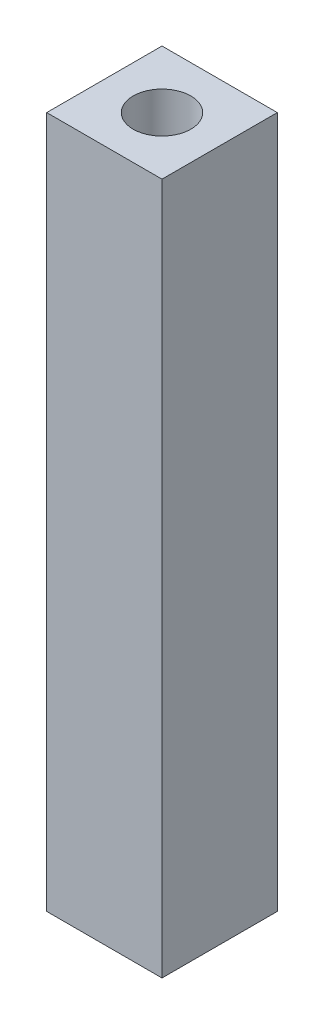
SolidWorks part; units mm, degrees
material "6061 Alloy"
ref_plane "Front Plane" through (0, 0, 0) normal (0, 0, 1) x (1, 0, 0)
ref_plane "Top Plane" through (0, 0, 0) normal (0, 1, 0) x (1, 0, 0)
ref_plane "Right Plane" through (0, 0, 0) normal (1, 0, 0) x (0, 0, -1)
sketch "Sketch1" plane through (0, 0, 0) normal (0, 1, 0) x (1, 0, 0)
  line L1 (-5, 5) -> (5, 5)
  line L2 (-5, 5) -> (-5, -5)
  line L3 (-5, -5) -> (5, -5)
  line L4 (5, 5) -> (5, -5)
  line L5 (-5, 5) -> (5, -5) construction
  line L6 (-5, -5) -> (5, 5) construction
  point P0 (0, 0)
  dimension "D1" = 10
  dimension "D2" = 10
extrude "Boss-Extrude1" add sketch "Sketch1" along normal blind 60
sketch "Sketch2" plane through (0, 60, 0) normal (0, 1, 0) x (1, 0, 0)
  circle A0 centre (0, 0) radius 2.5
  dimension "D1" = 5
extrude "Cut-Extrude1" cut sketch "Sketch2" against normal through all
